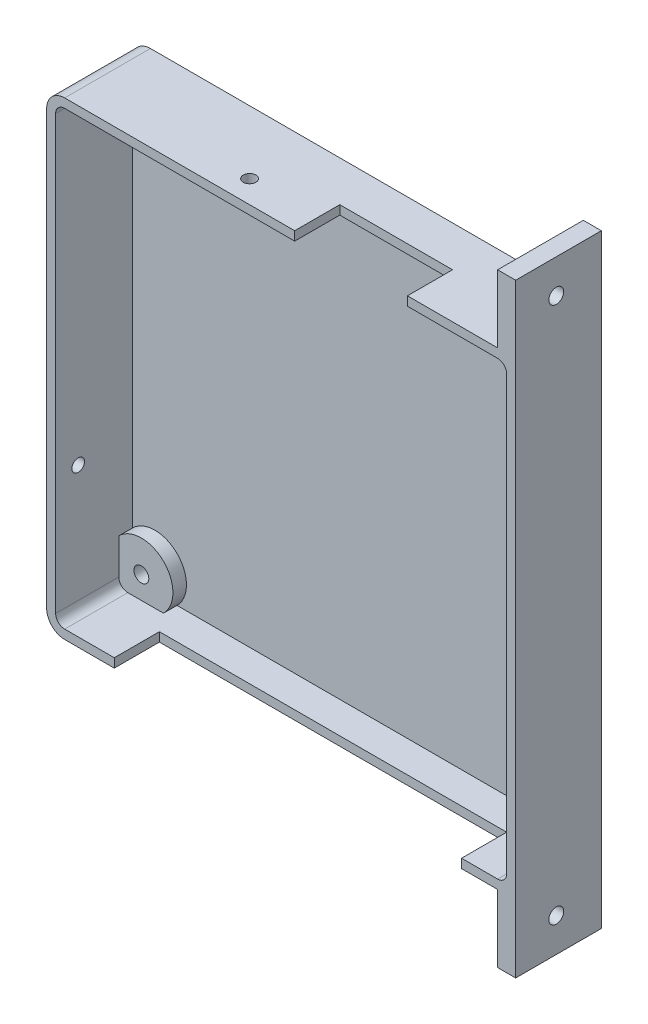
SolidWorks part; units mm, degrees
ref_plane "前视基准面" through (0, 0, 0) normal (0, 0, 1) x (1, 0, 0)
ref_plane "上视基准面" through (0, 0, 0) normal (0, 1, 0) x (1, 0, 0)
ref_plane "右视基准面" through (0, 0, 0) normal (1, 0, 0) x (0, 0, -1)
sketch "草图1" plane through (0, 0, 0) normal (0, 0, 1) x (1, 0, 0)
  line L1 (4, 0) -> (100, 0)
  line L2 (0, 4) -> (0, 100)
  line L3 (4, 104) -> (100, 104)
  line L4 (104, 4) -> (104, 100)
  circle A0 centre (7, 97) radius 1.65
  circle A1 centre (97, 97) radius 1.65
  circle A2 centre (7, 7) radius 1.65
  circle A3 centre (97, 7) radius 1.65
  arc A4 (0, 100) -> (4, 104) centre (4, 100) cw
  arc A5 (4, 0) -> (0, 4) centre (4, 4) cw
  arc A6 (100, 0) -> (104, 4) centre (100, 4) ccw
  arc A7 (100, 104) -> (104, 100) centre (100, 100) cw
  point P13 (52, 0)
  point P14 (104, 52)
  point P21 (0, 104)
  point P24 (0, 0)
  point P27 (104, 0)
  dimension "D6" = 45
  dimension "D7" = 3.3
  dimension "D8" = 4
  dimension "D1" = 104
  dimension "D2" = 104
  dimension "D3" = 90
  dimension "D4" = 90
  dimension "D5" = 45
extrude "凸台-拉伸1" add sketch "草图1" along normal blind 2
sketch "草图2" plane through (0, 0, 2) normal (0, 0, 1) x (1, 0, 0)
  line L0 (4, 0) -> (100, 0) construction
  line L1 (0, 100) -> (0, 4) construction
  line L2 (104, 4) -> (104, 100) construction
  circle A0 centre (7, 7) radius 1.65 construction
  circle A1 centre (97, 7) radius 1.65 construction
  circle A2 centre (97, 97) radius 1.65 construction
  circle A3 centre (7, 97) radius 1.65 construction
  circle A4 centre (7, 7) radius 1.65
  circle A5 centre (97, 7) radius 1.65
  circle A6 centre (97, 97) radius 1.65
  circle A7 centre (7, 97) radius 1.65
  circle A8 centre (7, 7) radius 7
  circle A9 centre (97, 7) radius 7
  circle A10 centre (7, 97) radius 7
  circle A11 centre (97, 97) radius 7
extrude "凸台-拉伸2" add sketch "草图2" along normal blind 3
sketch "草图3" plane through (0, 0, 2) normal (0, 0, 1) x (1, 0, 0)
  line L4 (100, 104) -> (4, 104)
  line L5 (104, 4) -> (104, 100)
  line L6 (4, 0) -> (100, 0)
  line L7 (0, 100) -> (0, 4)
  line L8 (100, 104) -> (4, 104)
  line L9 (104, 4) -> (104, 100)
  line L10 (4, 0) -> (100, 0)
  line L11 (0, 100) -> (0, 4)
  line L16 (100, 102) -> (4, 102)
  line L17 (102, 4) -> (102, 100)
  line L18 (4, 2) -> (100, 2)
  line L19 (2, 100) -> (2, 4)
  line L20 (100, 102) -> (4, 102)
  line L21 (102, 4) -> (102, 100)
  line L22 (4, 2) -> (100, 2)
  line L23 (2, 100) -> (2, 4)
  arc A4 (4, 104) -> (0, 100) centre (4, 100) ccw
  arc A5 (104, 100) -> (100, 104) centre (100, 100) ccw
  arc A6 (100, 0) -> (104, 4) centre (100, 4) ccw
  arc A7 (0, 4) -> (4, 0) centre (4, 4) ccw
  arc A8 (4, 104) -> (0, 100) centre (4, 100) ccw
  arc A9 (104, 100) -> (100, 104) centre (100, 100) ccw
  arc A10 (100, 0) -> (104, 4) centre (100, 4) ccw
  arc A11 (0, 4) -> (4, 0) centre (4, 4) ccw
  arc A16 (4, 102) -> (2, 100) centre (4, 100) ccw
  arc A17 (102, 100) -> (100, 102) centre (100, 100) ccw
  arc A18 (100, 2) -> (102, 4) centre (100, 4) ccw
  arc A19 (2, 4) -> (4, 2) centre (4, 4) ccw
  arc A20 (4, 102) -> (2, 100) centre (4, 100) ccw
  arc A21 (102, 100) -> (100, 102) centre (100, 100) ccw
  arc A22 (100, 2) -> (102, 4) centre (100, 4) ccw
  arc A23 (2, 4) -> (4, 2) centre (4, 4) ccw
  dimension "D1" = 0
  dimension "D2" = 2
extrude "凸台-拉伸3" add sketch "草图3" along normal blind 17
sketch "草图5" plane through (0, 0, 19) normal (0, 0, 1) x (1, 0, 0)
  line L0 (104, 4) -> (104, -15)
  line L1 (104, -15) -> (100, -15)
  line L2 (100, -15) -> (100, 0)
  line L3 (104, 100) -> (104, 119)
  line L4 (104, 119) -> (100, 119)
  line L5 (100, 119) -> (100, 104)
  arc A0 (100, 0) -> (104, 4) centre (100, 4) ccw construction
  arc A1 (104, 100) -> (100, 104) centre (100, 100) ccw construction
  arc A2 (100, 0) -> (104, 4) centre (100, 4) ccw
  arc A3 (104, 100) -> (100, 104) centre (100, 100) ccw
  dimension "D1" = 15
  dimension "D2" = 15
extrude "凸台-拉伸4" add sketch "草图5" against normal through all
sketch "草图6" plane through (100, 0, 0) normal (-1, 0, 0) x (0, 0, 1)
  line L0 (0, 0) -> (0, -15) construction
  line L1 (0, -15) -> (19, -15) construction
  line L2 (0, 119) -> (19, 119) construction
  line L3 (0, 119) -> (0, 104) construction
  circle A0 centre (10, -7.5) radius 1.65
  circle A1 centre (10, 111.5) radius 1.65
  dimension "D3" = 3.3
  dimension "D6" = 3.3
  dimension "D1" = 10
  dimension "D2" = 7.5
  dimension "D4" = 7.5
  dimension "D5" = 10
extrude "切除-拉伸1" cut sketch "草图6" against normal blind 10
sketch "草图7" plane through (0, 0, 19) normal (0, 0, 1) x (1, 0, 0)
  line L0 (4, 2) -> (100, 2) construction
  line L1 (15, 2) -> (92, 2)
  line L2 (15, 2) -> (15, 0)
  line L3 (15, 0) -> (92, 0)
  line L4 (92, 2) -> (92, 0)
  line L5 (4, 0) -> (100, 0) construction
  line L6 (102, 4) -> (102, 100) construction
  line L7 (0, 100) -> (0, 4) construction
  dimension "D1" = 10
  dimension "D2" = 15
extrude "切除-拉伸2" cut sketch "草图7" against normal blind 10
sketch "草图8" plane through (0, 104, 0) normal (0, 1, 0) x (1, 0, 0)
  line L0 (100, -19) -> (4, -19) construction
  line L1 (80, -19) -> (55, -19)
  line L2 (80, -19) -> (80, -9)
  line L3 (80, -9) -> (55, -9)
  line L4 (55, -19) -> (55, -9)
  line L5 (100, -19) -> (100, 0) construction
  dimension "D1" = 20
  dimension "D2" = 25
  dimension "D3" = 10
extrude "切除-拉伸3" cut sketch "草图8" against normal blind 10
sketch "草图9" plane through (0, 104, 0) normal (0, 1, 0) x (1, 0, 0)
  circle A0 centre (40, -14) radius 1.4
  dimension "D1" = 2.8
extrude "切除-拉伸4" cut sketch "草图9" against normal blind 22
sketch "草图10" plane through (0, 0, 0) normal (-1, 0, 0) x (0, 0, 1)
  circle A0 centre (14, 30) radius 1.4
  dimension "D1" = 2.8
extrude "切除-拉伸5" cut sketch "草图10" against normal blind 22
